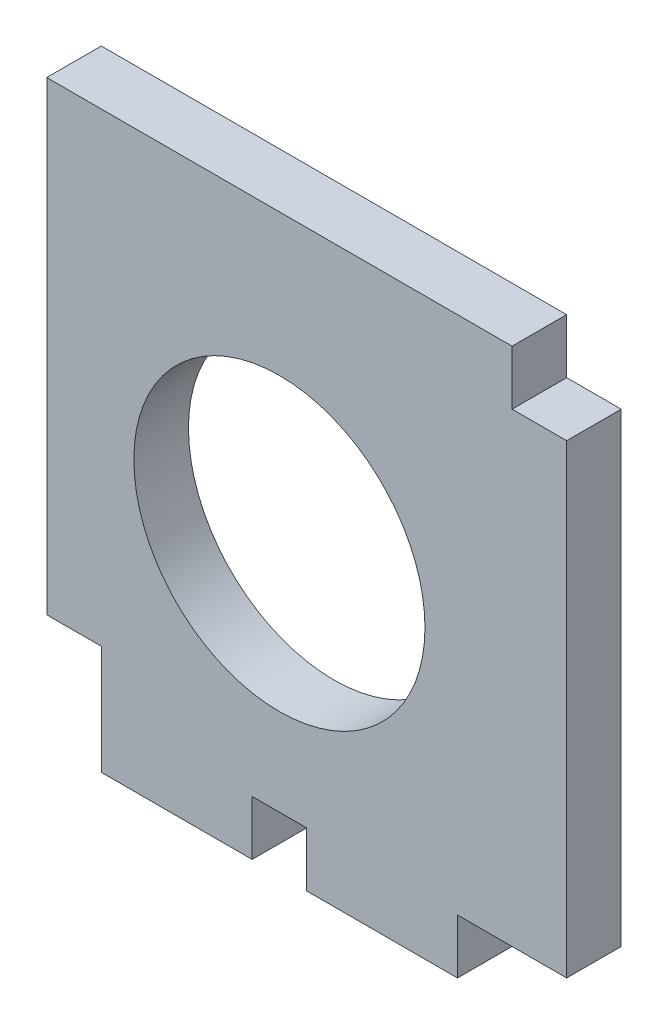
SolidWorks part; units mm, degrees
ref_plane "Front Plane" through (0, 0, 0) normal (0, 0, 1) x (1, 0, 0)
ref_plane "Top Plane" through (0, 0, 0) normal (0, 1, 0) x (1, 0, 0)
ref_plane "Right Plane" through (0, 0, 0) normal (1, 0, 0) x (0, 0, -1)
sketch "Sketch1" plane through (0, 0, 0) normal (0, 0, 1) x (1, 0, 0)
  line L0 (-20.3, -20.3) -> (-15.6929, -20.3) construction
  line L1 (-20.3, 34.9375) -> (-20.3, 54.9375) construction
  line L2 (20.3, -25.0625) -> (-20.3, -25.0625)
  line L3 (20.3, -25.0625) -> (20.3, 25.0625)
  line L4 (20.3, 25.0625) -> (-20.3, 25.0625)
  line L5 (-20.3, -25.0625) -> (-20.3, 25.0625)
  line L6 (-20.3, -20.3) -> (-15.5375, -20.3)
  line L7 (-20.3, -20.3) -> (-20.3, -15.5375)
  line L8 (20.3, -20.3) -> (20.3, 20.3) construction
  line L9 (-0.3, -25.0625) -> (19.7, -25.0625) construction
  line L10 (20.3, 20.3) -> (-20.3, 20.3) construction
  line L11 (-20.3, -20.3) -> (20.3, -20.3) construction
  line L12 (-20.3, -20.3) -> (20.3, -20.3)
  line L13 (-15.5375, -20.3) -> (-15.5375, -5.0625) construction
  line L14 (-20.3, -25.0625) -> (-15.5375, -25.0625)
  line L15 (-20.3, -25.0625) -> (-20.3, -20.3)
  line L16 (-20.3, -20.3) -> (-15.5375, -20.3)
  line L17 (-15.5375, -25.0625) -> (-15.5375, -20.3)
  line L18 (20.3, -25.0625) -> (15.5375, -25.0625)
  line L19 (20.3, -25.0625) -> (20.3, -20.3)
  line L20 (20.3, -20.3) -> (15.5375, -20.3)
  line L21 (15.5375, -25.0625) -> (15.5375, -20.3)
  line L22 (0, -25.0625) -> (0, -20.3) construction
  line L23 (25.3131, -20.3) -> (-15.6929, -20.3) construction
  line L24 (-2.3812, -20.3) -> (2.3813, -20.3)
  line L25 (-2.3812, -20.3) -> (-2.3812, -25.0625)
  line L26 (-2.3812, -25.0625) -> (2.3813, -25.0625)
  line L27 (2.3813, -20.3) -> (2.3813, -25.0625)
  line L28 (-2.3812, -20.3) -> (2.3813, -25.0625) construction
  line L29 (-2.3812, -25.0625) -> (2.3813, -20.3) construction
  line L30 (20.3, 20.3) -> (25.0625, 20.3)
  line L31 (20.3, 20.3) -> (20.3, -20.3)
  line L32 (20.3, -20.3) -> (25.0625, -20.3)
  line L33 (25.0625, 20.3) -> (25.0625, -20.3)
  line L34 (-20.3, -15.5375) -> (-15.5375, -15.5375)
  line L35 (-15.5375, -20.3) -> (-15.5375, -15.5375)
  point P23 (0, -22.6812)
  dimension "D1" = 4.7625
  dimension "D2" = 4.7625
  dimension "D3" = 4.7625
  dimension "D4" = 4.7625
  dimension "D5" = 4.7625
extrude "Boss-Extrude1" add sketch "Sketch1" along normal blind 4.7625 contours L25 L12 L17 L2 | L12 L27 L2 L21 | L5 L12 L3 L4 | L31 L30 L33 L32
sketch "Sketch2" plane through (0, 0, 4.7625) normal (0, 0, 1) x (1, 0, 0)
  circle A0 centre (0, 0) radius 12.7
  dimension "D1" = 25.4
extrude "Cut-Extrude1" cut sketch "Sketch2" against normal through all
